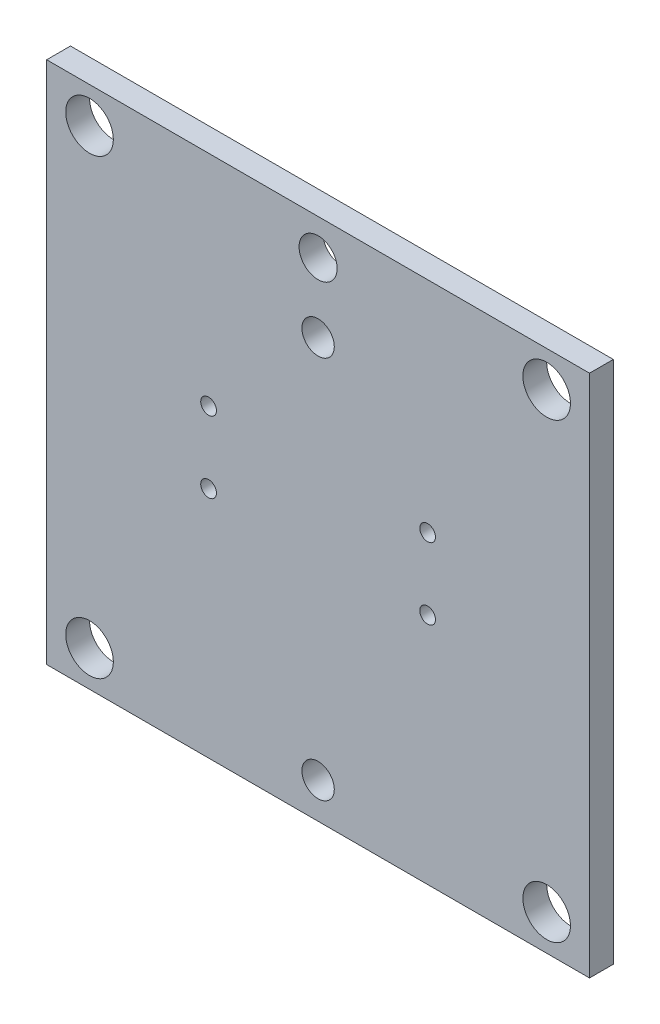
SolidWorks part; units mm, degrees
ref_plane "前视基准面" through (0, 0, 0) normal (0, 0, 1) x (1, 0, 0)
ref_plane "上视基准面" through (0, 0, 0) normal (0, 1, 0) x (1, 0, 0)
ref_plane "右视基准面" through (0, 0, 0) normal (1, 0, 0) x (0, 0, -1)
sketch "草图1" plane through (0, 0, 0) normal (0, 0, 1) x (1, 0, 0)
  line L0 (-1000, 0) -> (49000, 0) construction
  line L1 (-57, 55) -> (57, 55)
  line L2 (-57, 55) -> (-57, -55)
  line L3 (-57, -55) -> (57, -55)
  line L4 (57, 55) -> (57, -55)
  line L5 (-57, 55) -> (57, -55) construction
  line L6 (-57, -55) -> (57, 55) construction
  line L7 (0, -1000) -> (0, 49000) construction
  circle A0 centre (-23, 9) radius 2 construction
  circle A1 centre (-23, -9) radius 2 construction
  circle A3 centre (0, 47.5) radius 2 construction
  point P0 (0, 0)
  dimension "D3" = 46
  dimension "D4" = 23
  dimension "D7" = 7.5
  dimension "D1" = 110
  dimension "D2" = 114
extrude "凸台-拉伸2" add sketch "草图1" along normal mid plane 5
sketch "草图2" plane through (0, 0, 2.5) normal (0, 0, 1) x (1, 0, 0)
  line L0 (-1000, 0) -> (49000, 0) construction
  line L1 (0, -1000) -> (0, 49000) construction
  line L2 (-57, 55) -> (-57, -55) construction
  line L3 (57, 55) -> (-57, 55) construction
  circle A0 centre (-48, 47.5) radius 5
  dimension "D1" = 9
  dimension "D2" = 7.5
extrude "切除-拉伸1" cut sketch "草图2" against normal through all
mirror "镜向1" about plane through (0, 0, 0) normal (0, 1, 0) of "切除-拉伸1"
mirror "镜向2" about plane through (0, 0, 0) normal (1, 0, 0) of "镜向1", "切除-拉伸1"
sketch "草图4" plane through (0, 0, 2.5) normal (0, 0, 1) x (1, 0, 0)
  line L0 (57, 55) -> (-57, 55) construction
  line L1 (0, -1000) -> (0, 49000) construction
  circle A0 centre (-23, 9) radius 2 construction
  circle A1 centre (-23, -6) radius 2 construction
  circle A2 centre (0, 47.5) radius 2 construction
  circle A3 centre (0, 33) radius 2
  dimension "D1" = 46
  dimension "D2" = 23
  dimension "D3" = 15
  dimension "D4" = 7.5
  dimension "D5" = 22
hole_wizard "M4 螺纹孔的螺纹孔钻头1" positions "3D草图2" profile "草图5" hole size "M4" standard "GB" end condition through all
sketch3d "3D草图2"
  point P0 (-23, 9, 2.5)
  point P3 (-23, -6, 2.5)
sketch "草图5" plane through (-23, 9, 2.5) normal (1, 0, 0) x (0, -1, 0)
  line L0 (0, 0) -> (0, 5)
  line L1 (0, 5) -> (1.65, 5)
  line L2 (1.65, 5) -> (1.65, 0)
  line L5 (1.65, 0) -> (0, 0)
  line L11 (0, -6.35) -> (0, 107.95) construction
  dimension "通孔孔直径" = 3.3
  dimension "通孔孔深度" = 5
mirror "镜向4" about plane through (0, 0, 0) normal (1, 0, 0) of "M4 螺纹孔的螺纹孔钻头1"
hole_wizard "M8 螺纹孔的螺纹孔钻头3" positions "3D草图4" profile "草图7" hole size "M8" standard "GB" end condition through all
sketch3d "3D草图4"
  point P0 (0, 33, 2.5)
sketch "草图7" plane through (0, 33, 2.5) normal (1, 0, 0) x (0, -1, 0)
  line L0 (0, 0) -> (0, 5)
  line L1 (0, 5) -> (3.4, 5)
  line L2 (3.4, 5) -> (3.4, 0)
  line L5 (3.4, 0) -> (0, 0)
  line L11 (0, -6.35) -> (0, 107.95) construction
  dimension "通孔孔直径" = 6.8
  dimension "通孔孔深度" = 5
sketch "草图8" plane through (0, 0, 2.5) normal (0, 0, 1) x (1, 0, 0)
  circle A0 centre (0, 47.5) radius 4
extrude "切除-拉伸2" cut sketch "草图8" against normal through all
sketch "草图9" plane through (0, 0, 2.5) normal (0, 0, 1) x (1, 0, 0)
  line L0 (0, -201000) -> (0, 249000) construction
  circle A0 centre (0, -47.5) radius 2
hole_wizard "M8 螺纹孔的螺纹孔钻头4" positions "3D草图5" profile "草图10" hole size "M8" standard "GB" end condition through all
sketch3d "3D草图5"
  point P0 (0, -47.5, 2.5)
sketch "草图10" plane through (0, -47.5, 2.5) normal (1, 0, 0) x (0, -1, 0)
  line L0 (0, 0) -> (0, 5)
  line L1 (0, 5) -> (3.4, 5)
  line L2 (3.4, 5) -> (3.4, 0)
  line L5 (3.4, 0) -> (0, 0)
  line L11 (0, -6.35) -> (0, 107.95) construction
  dimension "通孔孔直径" = 6.8
  dimension "通孔孔深度" = 5
